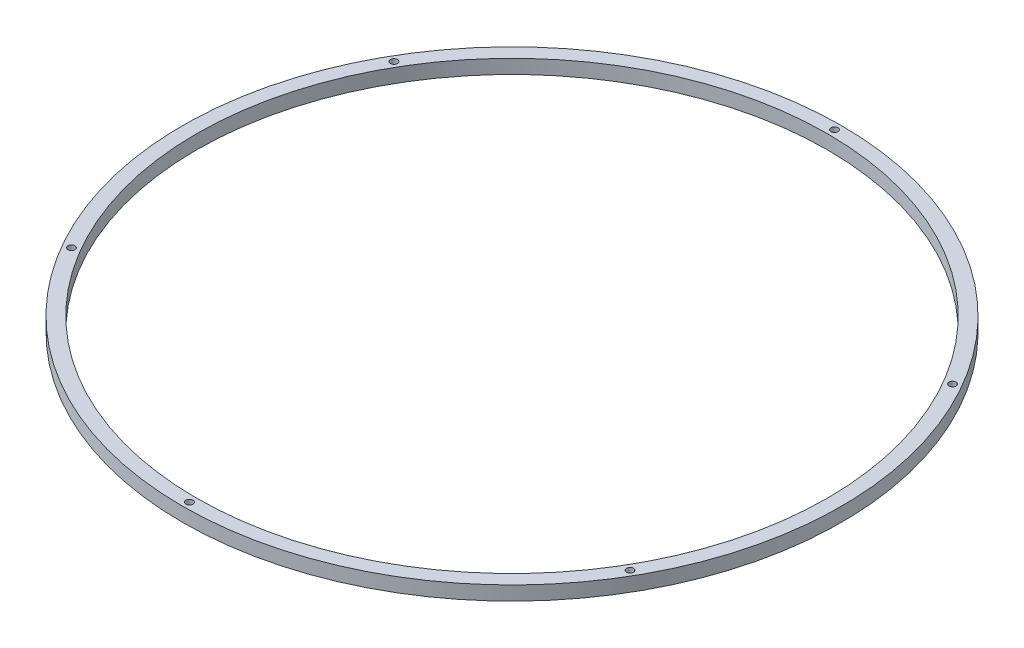
SolidWorks part; units mm, degrees
ref_plane "Front Plane" through (0, 0, 0) normal (0, 0, 1) x (1, 0, 0)
ref_plane "Top Plane" through (0, 0, 0) normal (0, 1, 0) x (1, 0, 0)
ref_plane "Right Plane" through (0, 0, 0) normal (1, 0, 0) x (0, 0, -1)
sketch "Sketch1" plane through (0, 0, 0) normal (0, 1, 0) x (1, 0, 0)
  circle A0 centre (0, 0) radius 225
  circle A1 centre (0, 0) radius 235
  dimension "D1" = 450
  dimension "D2" = 470
extrude "Boss-Extrude1" add sketch "Sketch1" along normal blind 10
sketch "Sketch2" plane through (0, 10, 0) normal (0, 1, 0) x (1, 0, 0)
  circle A0 centre (0, 0) radius 230
  dimension "D1" = 460
sketch "Sketch3" plane through (0, 10, 0) normal (0, 1, 0) x (1, 0, 0)
  circle A0 centre (0, 230) radius 2.5
  circle A1 centre (0, 0) radius 230 construction
  dimension "D1" = 5
extrude "Cut-Extrude1" cut sketch "Sketch3" against normal blind 10
pattern_circular "CirPattern1" count 6 over 360 about axis through (0, 0, 0) along (0, 1, 0) of "Cut-Extrude1"
